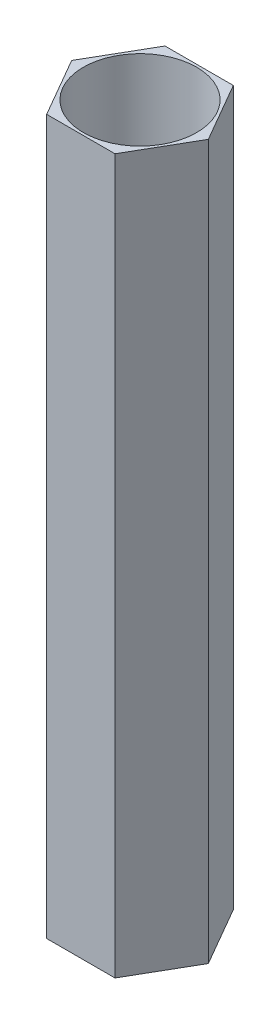
SolidWorks part; units mm, degrees
ref_plane "Front Plane" through (0, 0, 0) normal (0, 0, 1) x (1, 0, 0)
ref_plane "Top Plane" through (0, 0, 0) normal (0, 1, 0) x (1, 0, 0)
ref_plane "Right Plane" through (0, 0, 0) normal (1, 0, 0) x (0, 0, -1)
sketch "Sketch1" plane through (0, 0, 0) normal (0, 1, 0) x (1, 0, 0)
  line L1 (1.3568, -2.35) -> (2.7135, 0)
  line L2 (2.7135, 0) -> (1.3568, 2.35)
  line L3 (1.3568, 2.35) -> (-1.3568, 2.35)
  line L4 (-1.3568, 2.35) -> (-2.7135, 0)
  line L5 (-2.7135, 0) -> (-1.3568, -2.35)
  line L6 (-1.3568, -2.35) -> (1.3568, -2.35)
  circle A0 centre (0, 0) radius 2.35 construction
  circle A1 centre (0, 0) radius 2.25
  dimension "D1" = 4.5
  dimension "D2" = 4.7
extrude "Boss-Extrude1" add sketch "Sketch1" along normal blind 28.35
